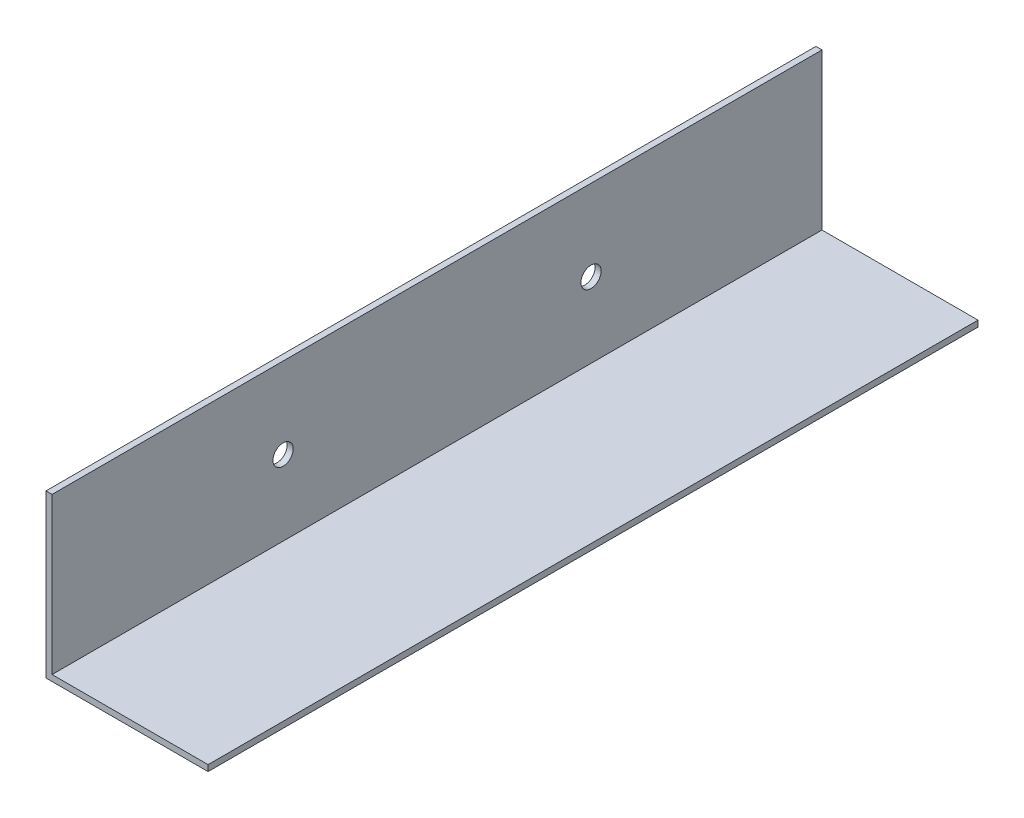
SolidWorks part; units mm, degrees
material "3.0205 (EN-AW 1200)"
ref_plane "Plan de face" through (0, 0, 0) normal (0, 0, 1) x (1, 0, 0)
ref_plane "Plan de dessus" through (0, 0, 0) normal (0, 1, 0) x (1, 0, 0)
ref_plane "Plan de droite" through (0, 0, 0) normal (1, 0, 0) x (0, 0, -1)
sketch "Esquisse1" plane through (0, 0, 0) normal (0, 0, 1) x (1, 0, 0)
  line L0 (0, 40) -> (0, 0)
  line L1 (0, 0) -> (40, 0)
  dimension "D1" = 40
  dimension "D2" = 40
extrude "Extru.-Mince1" add sketch "Esquisse1" along normal blind 190 thin thin type one direction reverse wall 1.5
sketch "Esquisse2" plane through (0, 0, 0) normal (-1, 0, 0) x (0, 0, 1)
  line L0 (95, 40) -> (95, 0) construction
  line L1 (190, 40) -> (0, 40) construction
  line L2 (190, 0) -> (0, 0) construction
  line L4 (133, 20) -> (57, 20) construction
  circle A0 centre (57, 20) radius 2.5
  circle A1 centre (133, 20) radius 2.5
  point P6 (95, 20)
  dimension "D2" = 5
  dimension "D1" = 76
extrude "Enlèv. mat.-Extru.1" cut sketch "Esquisse2" against normal through all
